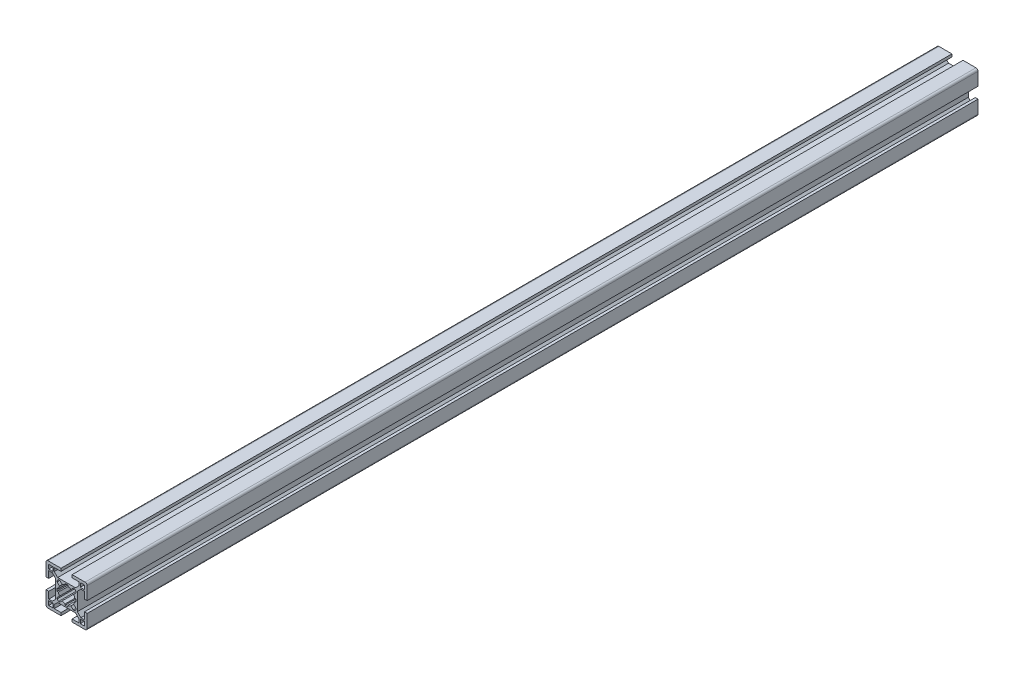
SolidWorks part; units mm, degrees
material "6063-T5"
ref_plane "Plano frontal" through (0, 0, 0) normal (0, 0, 1) x (1, 0, 0)
ref_plane "Plano superior" through (0, 0, 0) normal (0, 1, 0) x (1, 0, 0)
ref_plane "Plano direito" through (0, 0, 0) normal (1, 0, 0) x (0, 0, -1)
sketch "Esboço1" plane through (0, 0, 0) normal (0, 0, 1) x (1, 0, 0)
  line L0 (15, 13.5) -> (15, 4.05)
  line L1 (-13.5, 15) -> (-4.05, 15)
  line L8 (-9, 13) -> (-9, 10.4142)
  line L9 (-10, 13) -> (-10, 10)
  line L10 (-9, 13) -> (-4.05, 13)
  line L11 (-6.9, 1) -> (-6.9, 0)
  line L12 (-13, 13) -> (-10, 13)
  line L13 (-10.4142, 9) -> (-7.9, 6.4858)
  line L14 (-6.9, 1) -> (-5.9668, 1)
  line L15 (-15, 4.05) -> (-13, 4.05)
  line L16 (-6.4858, 7.9) -> (0, 7.9)
  line L17 (-4.9126, 6.9) -> (-3.1673, 5.1547)
  line L18 (-5.8279, 6.9) -> (-4.9126, 6.9)
  line L19 (-6.9, 5.8279) -> (-6.9, 4.9126)
  line L20 (-4.05, 15) -> (-4.05, 13)
  line L21 (13, 9) -> (10.4142, 9)
  line L22 (-1, 6.9) -> (-1, 5.9668)
  line L23 (-6.9, 4.9126) -> (-5.1547, 3.1673)
  line L24 (-5.8279, 6.9) -> (-6.9, 5.8279)
  line L25 (-7.9, 6.4858) -> (-7.9, 0)
  line L26 (13, 10) -> (10, 10)
  line L27 (-9, 10.4142) -> (-6.4858, 7.9)
  line L28 (13, 9) -> (13, 4.05)
  line L29 (-1, 6.9) -> (0, 6.9)
  line L30 (-6.4858, 6.9) -> (0, 6.9) construction
  line L31 (-13, 13) -> (-13, 10)
  line L32 (-13, 9) -> (-13, 4.05)
  line L33 (-15, 15) -> (-15, -15) construction
  line L34 (-15, 15) -> (15, 15) construction
  line L35 (-13, 10) -> (-10, 10)
  line L36 (-13, 9) -> (-10.4142, 9)
  line L37 (-13, 13) -> (13, 13) construction
  line L38 (-15, 13.5) -> (-15, 4.05)
  line L39 (1, 6.9) -> (0, 6.9)
  line L40 (13, 13) -> (13, 10)
  line L41 (-13, 13) -> (-13, -13) construction
  line L42 (9, 10.4142) -> (6.4858, 7.9)
  line L43 (1, 6.9) -> (1, 5.9668)
  line L44 (4.05, 15) -> (4.05, 13)
  line L45 (7.9, 6.4858) -> (7.9, 0)
  line L46 (6.9, 4.9126) -> (5.1547, 3.1673)
  line L47 (6.9, 5.8279) -> (6.9, 4.9126)
  line L48 (5.8279, 6.9) -> (4.9126, 6.9)
  line L49 (-7.9, 7.9) -> (7.9, 7.9) construction
  line L50 (15, 4.05) -> (13, 4.05)
  line L51 (6.9, 1) -> (5.9668, 1)
  line L52 (4.9126, 6.9) -> (3.1673, 5.1547)
  line L53 (6.9, 5.8279) -> (5.8279, 6.9)
  line L54 (6.4858, 7.9) -> (0, 7.9)
  line L55 (10.4142, 9) -> (7.9, 6.4858)
  line L56 (6.9, 1) -> (6.9, 0)
  line L57 (13, 13) -> (10, 13)
  line L58 (9, 13) -> (4.05, 13)
  line L59 (10, 13) -> (10, 10)
  line L60 (9, 13) -> (9, 10.4142)
  line L61 (13.5, 15) -> (4.05, 15)
  line L62 (13.5, -15) -> (4.05, -15)
  line L63 (9, -13) -> (9, -10.4142)
  line L64 (10, -13) -> (10, -10)
  line L65 (9, -13) -> (4.05, -13)
  line L66 (-7.9, 7.9) -> (-7.9, -7.9) construction
  line L67 (6.9, -1) -> (6.9, 0)
  line L68 (-15, -15) -> (15, -15) construction
  line L69 (15, 15) -> (15, -15) construction
  line L70 (13, 13) -> (13, -13) construction
  line L71 (-13, -13) -> (13, -13) construction
  line L72 (7.9, 7.9) -> (7.9, -7.9) construction
  line L73 (-7.9, -7.9) -> (7.9, -7.9) construction
  line L74 (13, -13) -> (10, -13)
  line L75 (10.4142, -9) -> (7.9, -6.4858)
  line L76 (6.9, -1) -> (5.9668, -1)
  line L77 (15, -4.05) -> (13, -4.05)
  line L78 (6.4858, -7.9) -> (0, -7.9)
  line L79 (4.9126, -6.9) -> (3.1673, -5.1547)
  line L80 (5.8279, -6.9) -> (4.9126, -6.9)
  line L81 (6.9, -5.8279) -> (6.9, -4.9126)
  line L82 (4.05, -15) -> (4.05, -13)
  line L83 (1, -6.9) -> (1, -5.9668)
  line L84 (6.9, -4.9126) -> (5.1547, -3.1673)
  line L85 (5.8279, -6.9) -> (6.9, -5.8279)
  line L86 (7.9, -6.4858) -> (7.9, 0)
  line L87 (9, -10.4142) -> (6.4858, -7.9)
  line L88 (1, -6.9) -> (0, -6.9)
  line L89 (13, -13) -> (13, -10)
  line L90 (13, -9) -> (13, -4.05)
  line L91 (13, -10) -> (10, -10)
  line L92 (13, -9) -> (10.4142, -9)
  line L93 (15, -13.5) -> (15, -4.05)
  line L94 (-15, -13.5) -> (-15, -4.05)
  line L95 (-13, -9) -> (-10.4142, -9)
  line L96 (-13, -10) -> (-10, -10)
  line L97 (-13, -9) -> (-13, -4.05)
  line L98 (-1, -6.9) -> (0, -6.9)
  line L99 (-13, -13) -> (-13, -10)
  line L100 (-9, -10.4142) -> (-6.4858, -7.9)
  line L101 (-1, -6.9) -> (-1, -5.9668)
  line L102 (-4.05, -15) -> (-4.05, -13)
  line L103 (-7.9, -6.4858) -> (-7.9, 0)
  line L104 (-6.9, -4.9126) -> (-5.1547, -3.1673)
  line L105 (-6.9, -5.8279) -> (-6.9, -4.9126)
  line L106 (-5.8279, -6.9) -> (-4.9126, -6.9)
  line L107 (-15, -4.05) -> (-13, -4.05)
  line L108 (-6.9, -1) -> (-5.9668, -1)
  line L109 (-4.9126, -6.9) -> (-3.1673, -5.1547)
  line L110 (-6.9, -5.8279) -> (-5.8279, -6.9)
  line L111 (-6.4858, -7.9) -> (0, -7.9)
  line L112 (-10.4142, -9) -> (-7.9, -6.4858)
  line L113 (-6.9, -1) -> (-6.9, 0)
  line L114 (-13, -13) -> (-10, -13)
  line L115 (-9, -13) -> (-4.05, -13)
  line L116 (-10, -13) -> (-10, -10)
  line L117 (-9, -13) -> (-9, -10.4142)
  line L118 (-13.5, -15) -> (-4.05, -15)
  arc A0 (-1, 5.9668) -> (-3.1673, 5.1547) centre (0, 0) ccw
  arc A1 (-5.9668, 1) -> (-5.1547, 3.1673) centre (0, 0) cw
  arc A2 (-13.5, 15) -> (-15, 13.5) centre (-13.5, 13.5) ccw
  arc A3 (5.9668, 1) -> (5.1547, 3.1673) centre (0, 0) ccw
  arc A4 (1, 5.9668) -> (3.1673, 5.1547) centre (0, 0) cw
  arc A5 (15, 13.5) -> (13.5, 15) centre (13.5, 13.5) ccw
  arc A6 (1, -5.9668) -> (3.1673, -5.1547) centre (0, 0) ccw
  arc A7 (5.9668, -1) -> (5.1547, -3.1673) centre (0, 0) cw
  arc A8 (13.5, -15) -> (15, -13.5) centre (13.5, -13.5) ccw
  arc A9 (-5.9668, -1) -> (-5.1547, -3.1673) centre (0, 0) ccw
  arc A10 (-1, -5.9668) -> (-3.1673, -5.1547) centre (0, 0) cw
  arc A11 (-15, -13.5) -> (-13.5, -15) centre (-13.5, -13.5) ccw
  point P139 (0, 0)
  dimension "D1" = 4
extrude "Ressalto-extrusão1" add sketch "Esboço1" along normal mid plane 650
